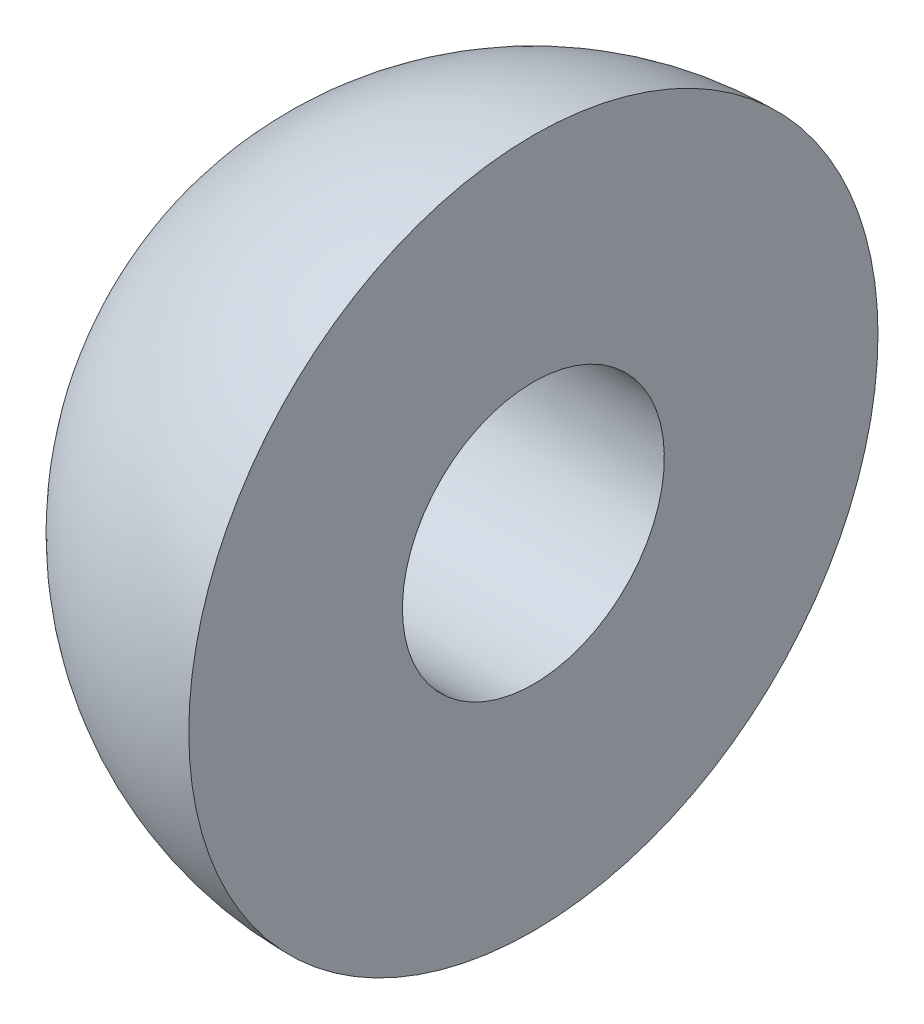
SolidWorks part; units mm, degrees
ref_plane "前视基准面" through (0, 0, 0) normal (0, 0, 1) x (1, 0, 0)
ref_plane "上视基准面" through (0, 0, 0) normal (0, 1, 0) x (1, 0, 0)
ref_plane "右视基准面" through (0, 0, 0) normal (1, 0, 0) x (0, 0, -1)
sketch "草图1" plane through (0, 0, 0) normal (1, 0, 0) x (0, 0, -1)
  line L0 (-2.5, 0) -> (2.5, 0) construction
  line L1 (-2.5, 0) -> (2.5, 0)
  arc A0 (-2.5, 0) -> (2.5, 0) centre (0, 0) ccw
  dimension "D1" = 5
revolve "旋转1" add sketch "草图1" angle 180 about L0
sketch "草图2" plane through (0, 0, 0) normal (1, 0, 0) x (0, 0, -1)
  circle A0 centre (0, 0) radius 0.95
  dimension "D1" = 1.9
extrude "切除-拉伸1" cut sketch "草图2" against normal through all
